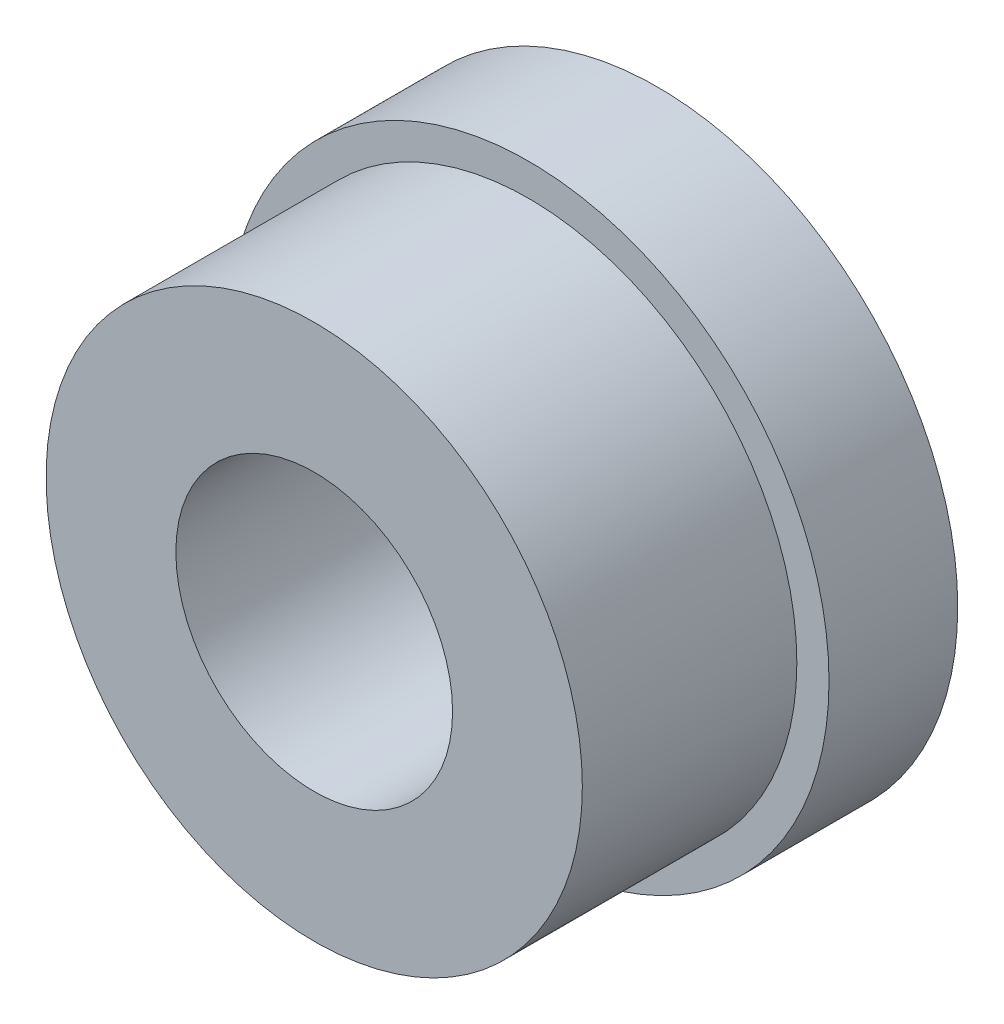
SolidWorks part; units mm, degrees
material "PLA"
ref_plane "前视基准面" through (0, 0, 0) normal (0, 0, 1) x (1, 0, 0)
ref_plane "上视基准面" through (0, 0, 0) normal (0, 1, 0) x (1, 0, 0)
ref_plane "右视基准面" through (0, 0, 0) normal (1, 0, 0) x (0, 0, -1)
other "Configuration Table"
sketch "草图1" plane through (0, 0, 0) normal (0, 0, 1) x (1, 0, 0)
  line L1 (-4.35, 4.35) -> (4.35, 4.35) construction
  line L2 (-4.35, 4.35) -> (-4.35, -4.35) construction
  line L3 (-4.35, -4.35) -> (4.35, -4.35) construction
  line L4 (4.35, 4.35) -> (4.35, -4.35) construction
  line L5 (-4.35, 4.35) -> (4.35, -4.35) construction
  line L6 (-4.35, -4.35) -> (4.35, 4.35) construction
  circle A0 centre (0, 0) radius 12.5
  circle A1 centre (0, 0) radius 6.45
  dimension "D3" = 25
  dimension "D4" = 12.9
  dimension "D1" = 8.7
  dimension "D2" = 8.7
extrude "凸台-拉伸1" add sketch "草图1" along normal blind 10
sketch "草图2" plane through (0, 0, 0) normal (0, 0, -1) x (-1, 0, 0)
  circle A0 centre (0, 0) radius 14
  circle A1 centre (0, 0) radius 6.45 construction
  circle A2 centre (0, 0) radius 6.45
  dimension "D1" = 28
extrude "凸台-拉伸2" add sketch "草图2" along normal blind 6
sketch "草图3" plane through (0, 0, -6) normal (0, 0, -1) x (-1, 0, 0)
  circle A0 centre (0, 0) radius 25
  dimension "D1" = 50
extrude "凸台-拉伸3" [suppressed] add sketch "草图3" along normal blind 10
sketch "草图4" [suppressed] plane through (0, 0, -6) normal (0, 0, 1) x (1, 0, 0)
  line L4 (7.55, 7.55) -> (-7.55, 7.55)
  line L5 (-7.55, 7.55) -> (-7.55, -7.55)
  line L6 (-7.55, -7.55) -> (7.55, -7.55)
  line L7 (7.55, -7.55) -> (7.55, 7.55)
  line L8 (7.55, 7.55) -> (-7.55, 7.55)
  line L9 (-7.55, 7.55) -> (-7.55, -7.55)
  line L10 (-7.55, -7.55) -> (7.55, -7.55)
  line L11 (7.55, -7.55) -> (7.55, 7.55)
  dimension "D1" = 0
extrude "切除-拉伸1" [suppressed] cut sketch "草图4" against normal blind 16
